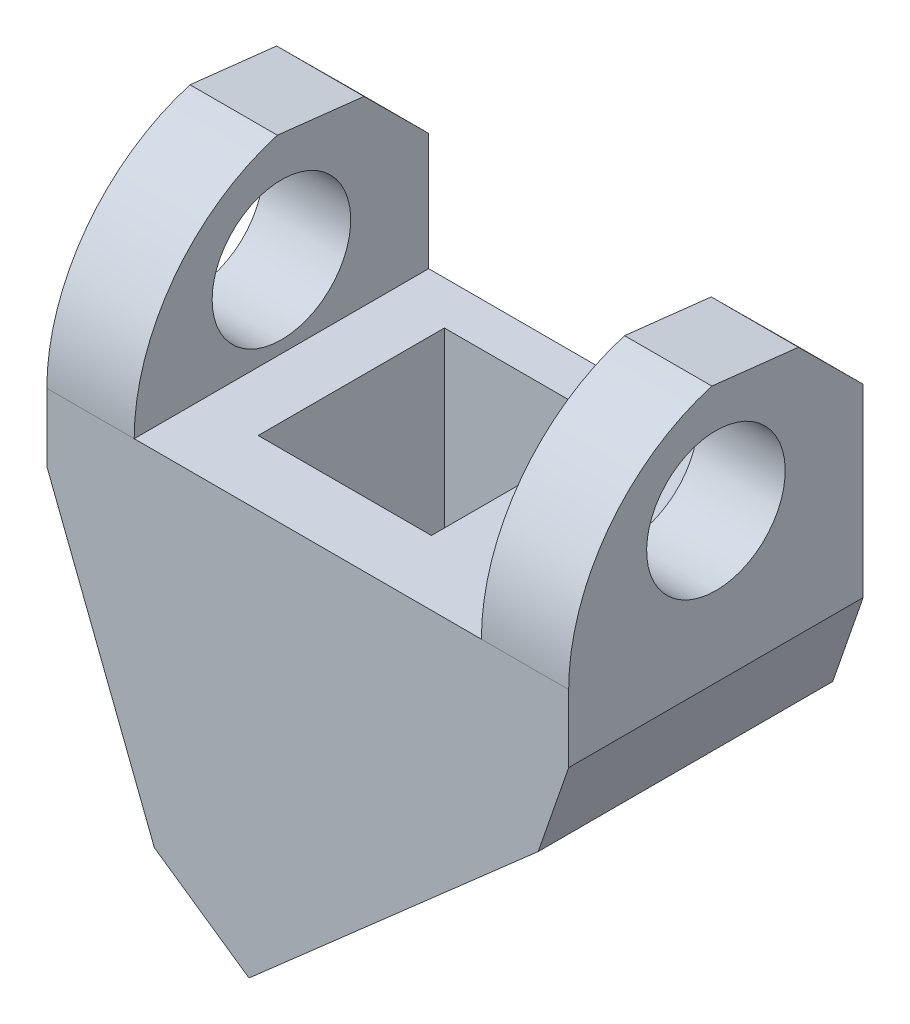
SolidWorks part; units mm, degrees
ref_plane "Front plane" through (0, 0, 0) normal (0, 0, 1) x (1, 0, 0)
ref_plane "Base plane" through (0, 0, 0) normal (0, 1, 0) x (1, 0, 0)
ref_plane "Right plane" through (0, 0, 0) normal (1, 0, 0) x (0, 0, -1)
sketch "Sketch1" plane through (0, 0, 0) normal (0, 0, 1) x (1, 0, 0)
  line L0 (-30.544, 100.8614) -> (-25.502, 100.8614)
  line L1 (-25.502, 100.8614) -> (-25.502, 89.7634)
  line L2 (-25.502, 89.7634) -> (-5.4595, 89.7634)
  line L3 (-5.4595, 89.7634) -> (-5.4595, 100.8614)
  line L4 (-5.4595, 100.8614) -> (-0.4211, 100.8614)
  line L5 (-0.4211, 100.8614) -> (-0.4211, 85.8614)
  line L6 (-0.4211, 85.8614) -> (-2.1796, 80.7846)
  line L7 (-2.1796, 80.7846) -> (-18.8741, 66.1178)
  line L8 (-18.8741, 66.1178) -> (-24.337, 69.8995)
  line L9 (-24.337, 69.8995) -> (-30.544, 85.8614)
  line L10 (-30.544, 85.8614) -> (-30.544, 100.8614)
  dimension "D1" = 5.042
  dimension "D2" = 5.0383
  dimension "D4" = 15
  dimension "D6" = 5.3727
  dimension "D7" = 22.2221
  dimension "D8" = 6.6441
  dimension "D9" = 15.9619
  dimension "D10" = 158.751
  dimension "D11" = 145.943
  dimension "D12" = 104.006
extrude "Boss-Extrude1" add sketch "Sketch1" along normal blind 17
sketch "Sketch2" plane through (-25.502, 0, 0) normal (1, 0, 0) x (0, 0, -1)
  line L0 (0, 89.7634) -> (-17, 89.7634)
  line L1 (0, 89.7634) -> (0, 96.5274)
  line L2 (0, 96.5274) -> (-3.734, 100.2414)
  line L3 (-3.734, 100.2414) -> (-8.734, 100.8034)
  line L5 (-17, 89.7634) -> (-17, 100.8614) construction
  line L6 (-17, 89.7634) -> (-17, 100.8614)
  line L9 (-17, 100.8614) -> (0, 100.8614)
  line L10 (0, 100.8614) -> (0, 96.5274)
  arc A0 (-8.734, 100.8034) -> (-17, 89.7634) centre (-5.4945, 89.7634) ccw
  line M5 (0, 89.7634) -> (0, 100.8614)
  line M6 (0, 100.8614) -> (-17, 100.8614)
  line M7 (-17, 100.8614) -> (-17, 89.7634)
  dimension "D1" = 17
  dimension "D2" = 134.846
  dimension "D3" = 141.567
  dimension "D5" = 9.9953
  dimension "D6" = 6.764
  dimension "D7" = 5
extrude "Cut-Extrude1" cut sketch "Sketch2" against normal blind 15 and the other way blind 44 contours A0 L3 L2 M5 M6 M7
sketch "Sketch3" plane through (-41.0054, 46.6746, 0) normal (0.66, -0.7513, 0) x (0.7513, 0.66, 0)
  line L0 (33.4795, 17) -> (33.4795, 0) construction
  line L1 (29.459, 17) -> (51.6812, 17) construction
  line L2 (29.459, 0) -> (51.6812, 0) construction
  line L3 (33.4795, 0) -> (42.9531, 0) construction
  line L4 (42.9531, 0) -> (42.9531, 17) construction
  line L5 (42.9531, 17) -> (33.4795, 17) construction
  line L6 (33.4795, 13.2611) -> (33.4795, 2.5149)
  line L7 (33.4795, 2.5149) -> (42.9531, 2.5149)
  line L8 (42.9531, 2.5149) -> (42.9531, 13.2611)
  line L9 (42.9531, 13.2611) -> (33.4795, 13.2611)
  dimension "D1" = 4.0205
  dimension "D2" = 9.4736
  dimension "D3" = 10.7461
  dimension "D4" = 3.7389
ref_plane "Plane1" through (0, 0, 10) normal (0, 0, 1) x (1, 0, 0)
sketch "Sketch4" plane through (0, 0, 10) normal (0, 0, 1) x (1, 0, 0)
  line L0 (-14.8065, 69.6914) -> (-22.1166, 75.2189)
  line L1 (-15.8537, 68.7714) -> (-8.7366, 75.024) construction
  line L2 (-18.8741, 66.1178) -> (-2.1796, 80.7846) construction
sweep "Cut-Sweep1" cut profiles "Sketch3" path "Sketch4"
sketch "Sketch5" plane through (0, 89.7634, 0) normal (0, 1, 0) x (1, 0, 0)
  line L0 (-22.084, 0) -> (-22.084, -17) construction
  line L1 (-5.4595, 0) -> (-25.502, 0) construction
  line L2 (-5.4595, -17) -> (-25.502, -17) construction
  line L3 (-12.084, 0) -> (-12.084, -17) construction
  line L4 (-22.084, -2.51) -> (-12.084, -2.51)
  line L5 (-22.084, -13.26) -> (-12.084, -13.26)
  line L6 (-30.544, -8.734) -> (-30.544, -3.734) construction
  line L7 (-22.084, -2.51) -> (-22.084, -13.26)
  line L8 (-12.084, -2.51) -> (-12.084, -13.26)
  dimension "D1" = 8.46
  dimension "D2" = 3.74
  dimension "D3" = 10.75
  dimension "D4" = 10
extrude "Cut-Extrude4" cut sketch "Sketch5" against normal up to surface (23.8425 mm away)
ref_plane "Plane2" through (-15.4807, 0, 0) normal (-1, 0, 0) x (0, 0, 1)
sketch "Sketch6" plane through (-15.4807, 0, 0) normal (-1, 0, 0) x (0, 0, 1)
  line L0 (0, 85.8614) -> (17, 85.8614) construction
  line L1 (8.5, 85.8614) -> (8.5, 94.4593) construction
  circle A0 centre (8.5, 94.4593) radius 4
  dimension "D1" = 8.5979
  dimension "D2" = 8
extrude "Cut-Extrude5" cut sketch "Sketch6" against normal through all both and the other way through all
